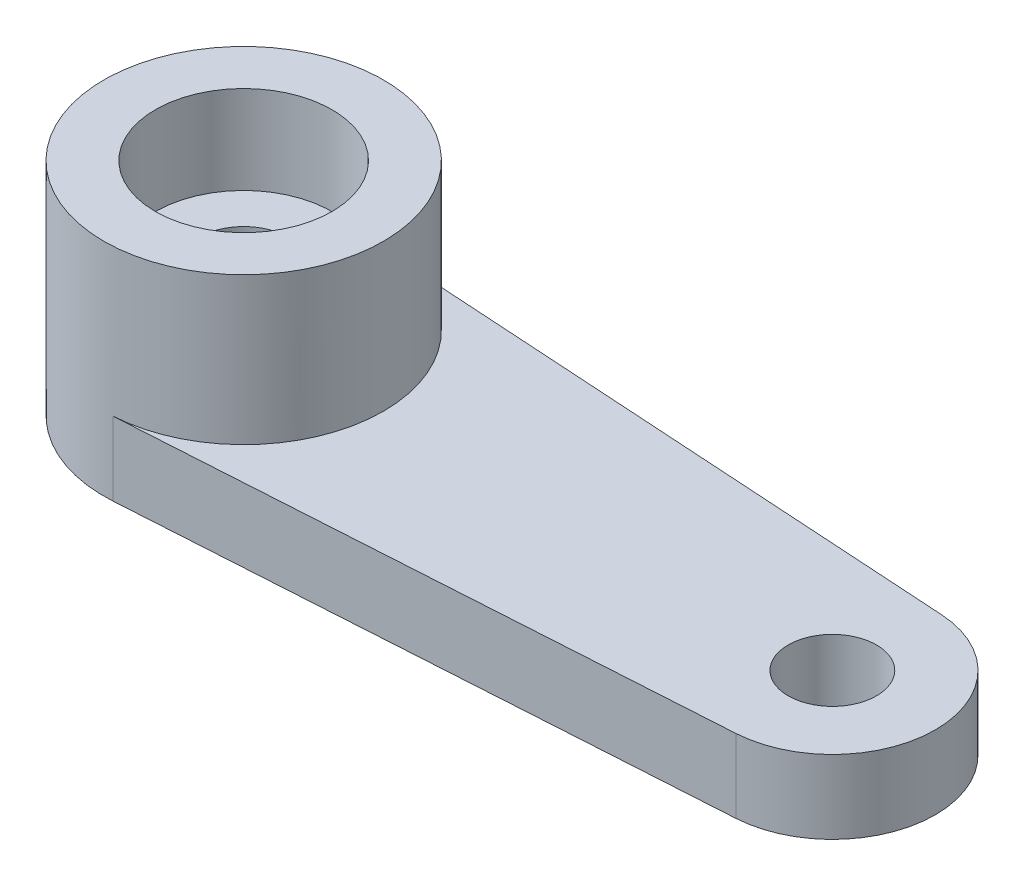
SolidWorks part; units mm, degrees
ref_plane "前视基准面" through (0, 0, 0) normal (0, 0, 1) x (1, 0, 0)
ref_plane "上视基准面" through (0, 0, 0) normal (0, 1, 0) x (1, 0, 0)
ref_plane "右视基准面" through (0, 0, 0) normal (1, 0, 0) x (0, 0, -1)
sketch "草图1" plane through (0, 0, 0) normal (0, 1, 0) x (1, 0, 0)
  line L0 (0, 0) -> (20, 0) construction
  line L1 (0.2969, 4.7407) -> (20.2188, 3.4932)
  line L2 (0.2969, -4.7407) -> (20.2188, -3.4932)
  arc A0 (0.2969, 4.7407) -> (0.2969, -4.7407) centre (0, 0) ccw
  circle A2 centre (0, 0) radius 3
  circle A3 centre (20, 0) radius 1.5
  arc A4 (20.2188, 3.4932) -> (20.2188, -3.4932) centre (20, 0) cw
  point P3 (10, 0)
  point P13 (21.5619, 3.4124)
  point P14 (21.5619, -3.2327)
  point P15 (0, 0)
  dimension "D1" = 6
  dimension "D2" = 4.75
  dimension "D4" = 3.5
  dimension "D5" = 3
  dimension "D3" = 20
extrude "凸台-拉伸1" add sketch "草图1" along normal blind 2.5
sketch "草图2" plane through (0, 2.5, 0) normal (0, 1, 0) x (1, 0, 0)
  circle A0 centre (0, 0) radius 4.75
extrude "凸台-拉伸2" add sketch "草图2" along normal blind 5
sketch "草图3" plane through (0, 7.5, 0) normal (0, 1, 0) x (1, 0, 0)
  circle A0 centre (0, 0) radius 3
  dimension "D1" = 6
extrude "切除-拉伸1" cut sketch "草图3" against normal blind 3
sketch "草图4" plane through (0, 2.5, 0) normal (0, -1, 0) x (1, 0, 0)
  circle A0 centre (0, 0) radius 1.5
  dimension "D1" = 3
extrude "切除-拉伸2" cut sketch "草图4" against normal blind 3
sketch "草图5" plane through (0, 0, 0) normal (0, -1, 0) x (1, 0, 0)
  line L0 (0, 0) -> (20, 0) construction
